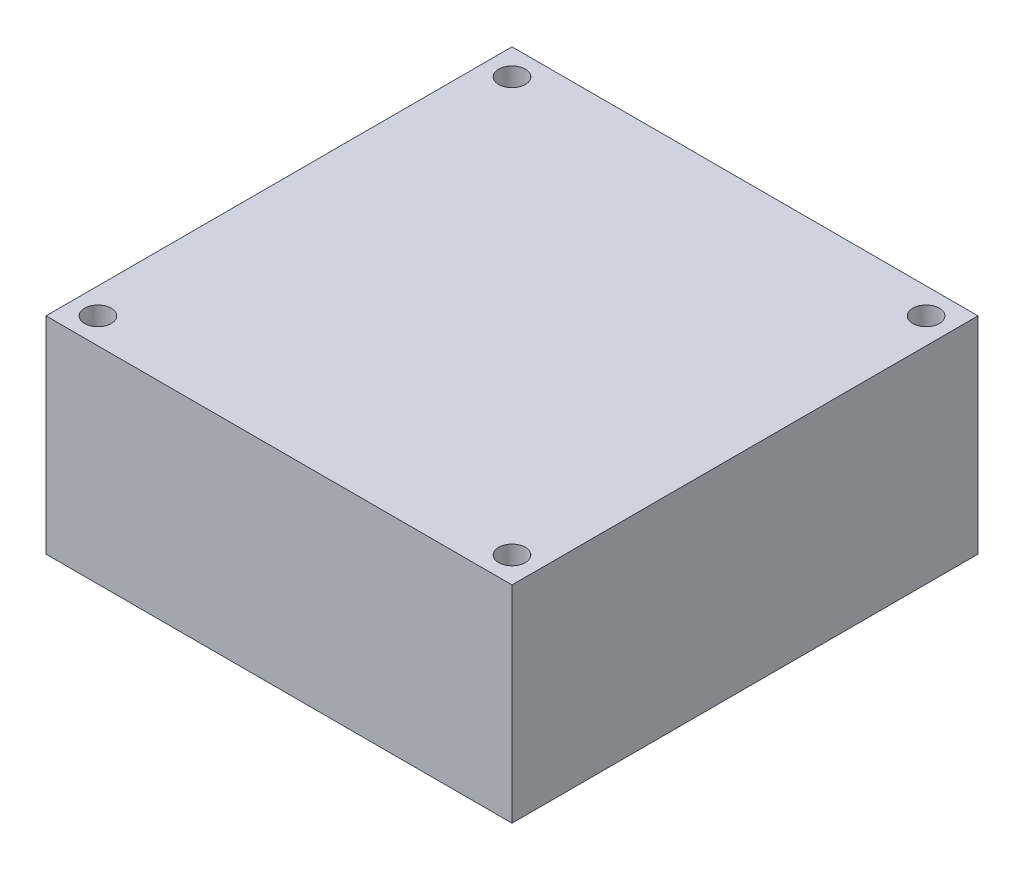
SolidWorks part; units mm, degrees
ref_plane "Front Plane" through (0, 0, 0) normal (0, 0, 1) x (1, 0, 0)
ref_plane "Top Plane" through (0, 0, 0) normal (0, 1, 0) x (1, 0, 0)
ref_plane "Right Plane" through (0, 0, 0) normal (1, 0, 0) x (0, 0, -1)
sketch "Sketch1" plane through (0, 0, 0) normal (0, 1, 0) x (1, 0, 0)
  line L1 (-35, 35) -> (35, 35)
  line L2 (-35, 35) -> (-35, -35)
  line L3 (-35, -35) -> (35, -35)
  line L4 (35, 35) -> (35, -35)
  line L5 (-35, 35) -> (35, -35) construction
  line L6 (-35, -35) -> (35, 35) construction
  point P0 (0, 0)
  dimension "D1" = 70
extrude "Boss-Extrude1" add sketch "Sketch1" along normal blind 31
sketch "Sketch2" plane through (0, 31, 0) normal (0, 1, 0) x (1, 0, 0)
  line L1 (31.1, 31.1) -> (-31.1, 31.1) construction
  line L2 (31.1, 31.1) -> (31.1, -31.1) construction
  line L3 (31.1, -31.1) -> (-31.1, -31.1) construction
  line L4 (-31.1, 31.1) -> (-31.1, -31.1) construction
  line L5 (31.1, 31.1) -> (-31.1, -31.1) construction
  line L6 (31.1, -31.1) -> (-31.1, 31.1) construction
  circle A0 centre (-31.1, 31.1) radius 2
  circle A1 centre (31.1, 31.1) radius 2
  circle A2 centre (31.1, -31.1) radius 2
  circle A3 centre (-31.1, -31.1) radius 2
  point P8 (0, 0)
  dimension "D2" = 4
  dimension "D1" = 62.2
extrude "Cut-Extrude1" cut sketch "Sketch2" against normal through all
